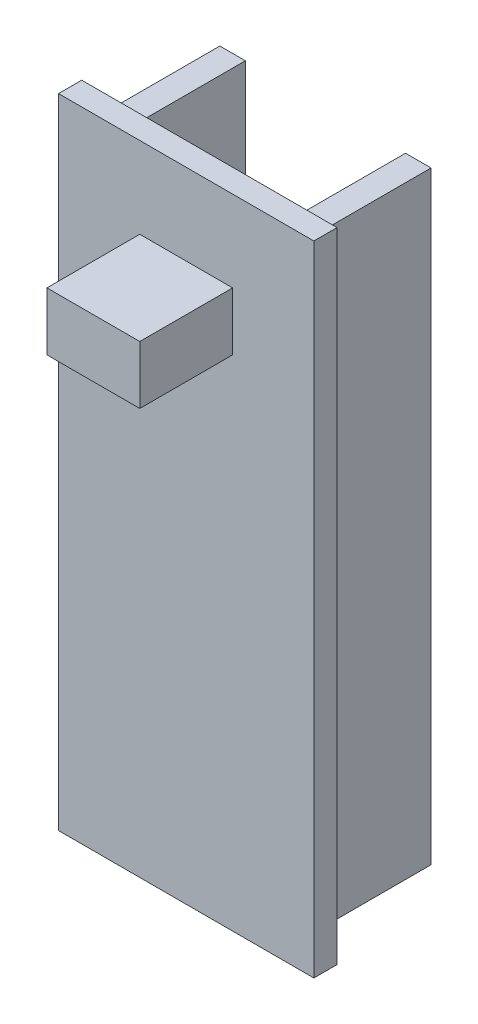
SolidWorks part; units mm, degrees
ref_plane "前视基准面" through (0, 0, 0) normal (0, 0, 1) x (1, 0, 0)
ref_plane "上视基准面" through (0, 0, 0) normal (0, 1, 0) x (1, 0, 0)
ref_plane "右视基准面" through (0, 0, 0) normal (1, 0, 0) x (0, 0, -1)
sketch "草图1" plane through (0, 0, 0) normal (0, 0, 1) x (1, 0, 0)
  line L1 (-11, -27.5) -> (11, -27.5)
  line L2 (-11, -27.5) -> (-11, 27.5)
  line L3 (-11, 27.5) -> (11, 27.5)
  line L4 (11, -27.5) -> (11, 27.5)
  line L5 (-11, -27.5) -> (11, 27.5) construction
  line L6 (-11, 27.5) -> (11, -27.5) construction
  point P0 (0, 0)
  dimension "D1" = 22
  dimension "D2" = 55
sketch "草图2" plane through (0, 0, 0) normal (0, 0, 1) x (1, 0, 0)
  line L0 (-8, 0) -> (8, 0) construction
  line L1 (0, -1000) -> (0, 49000) construction
  line L2 (9.1, -26) -> (6.9, -26)
  line L3 (-9.1, -26) -> (-6.9, -26)
  line L4 (-9.1, -26) -> (-9.1, 26)
  line L5 (-9.1, 26) -> (-6.9, 26)
  line L6 (-6.9, -26) -> (-6.9, 26)
  line L7 (-9.1, -26) -> (-6.9, 26) construction
  line L8 (-9.1, 26) -> (-6.9, -26) construction
  line L9 (6.9, -26) -> (6.9, 26)
  line L10 (9.1, -26) -> (9.1, 26)
  line L11 (9.1, 26) -> (6.9, 26)
  dimension "D1" = 16
  dimension "D2" = 2.2
  dimension "D3" = 52
extrude "凸台-拉伸1" add sketch "草图1" along normal blind 2
extrude "凸台-拉伸2" add sketch "草图2" against normal blind 10
ref_plane "基准面1" through (0, 0, 2) normal (0, 0, 1) x (1, 0, 0)
sketch "草图4" plane through (0, 0, 2) normal (0, 0, 1) x (1, 0, 0)
  line L0 (0, 0) -> (0, 18) construction
  line L2 (-4, 15.5) -> (4, 15.5)
  line L3 (-4, 15.5) -> (-4, 20.5)
  line L4 (-4, 20.5) -> (4, 20.5)
  line L5 (4, 15.5) -> (4, 20.5)
  line L6 (-4, 15.5) -> (4, 20.5) construction
  line L7 (-4, 20.5) -> (4, 15.5) construction
  dimension "D1" = 18
  dimension "D2" = 5
  dimension "D3" = 8
extrude "凸台-拉伸3" add sketch "草图4" along normal blind 8
